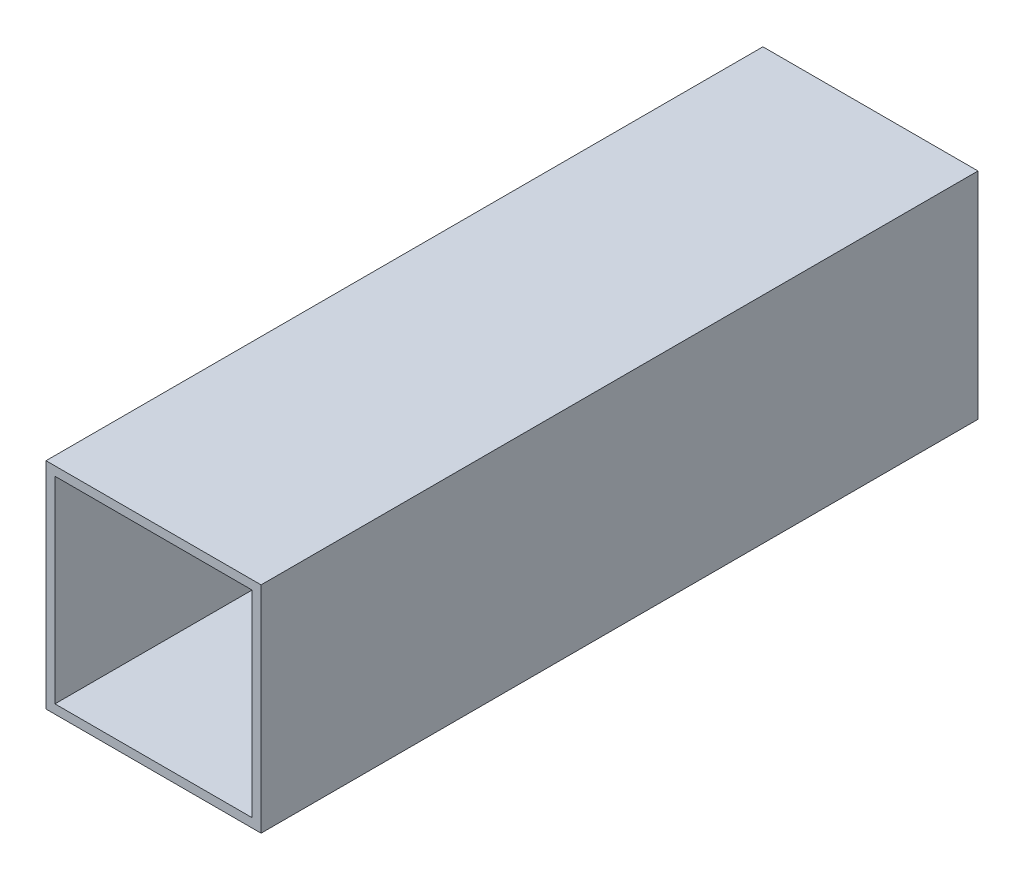
SolidWorks part; units mm, degrees
material "Plain Carbon Steel"
ref_plane "Front Plane" through (0, 0, 0) normal (0, 0, 1) x (1, 0, 0)
ref_plane "Top Plane" through (0, 0, 0) normal (0, 1, 0) x (1, 0, 0)
ref_plane "Right Plane" through (0, 0, 0) normal (1, 0, 0) x (0, 0, -1)
sketch "Sketch2" plane through (0, 0, 0) normal (0, 0, 1) x (1, 0, 0)
  line L0 (0, 19.05) -> (1.5875, 19.05) construction
  line L1 (0, 0) -> (38.1, 0)
  line L2 (0, 0) -> (0, 38.1)
  line L3 (0, 38.1) -> (38.1, 38.1)
  line L4 (38.1, 0) -> (38.1, 38.1)
  line L5 (1.5875, 1.5875) -> (36.5125, 1.5875)
  line L6 (1.5875, 1.5875) -> (1.5875, 36.5125)
  line L7 (1.5875, 36.5125) -> (36.5125, 36.5125)
  line L8 (36.5125, 1.5875) -> (36.5125, 36.5125)
  line L9 (19.05, 36.5125) -> (19.05, 38.1) construction
  line L10 (36.5125, 19.05) -> (38.1, 19.05) construction
  line L11 (19.05, 0) -> (19.05, 1.5875) construction
  dimension "D1" = 38.1
  dimension "D2" = 1.5875
  dimension "D3" = 38.1
extrude "Boss-Extrude1" add sketch "Sketch2" along normal blind 127
